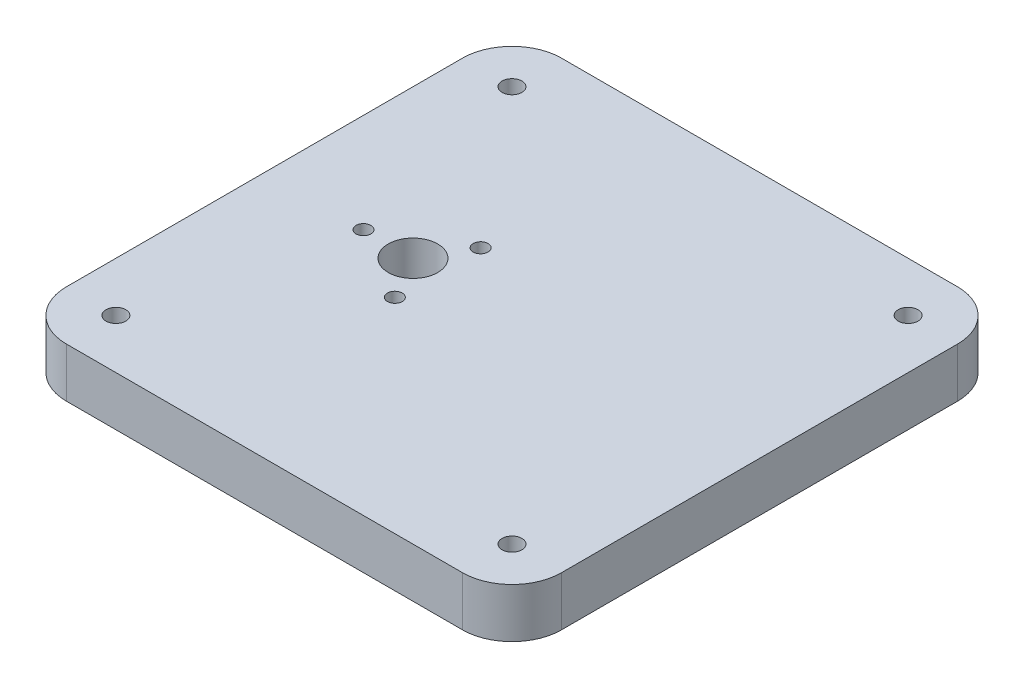
SolidWorks part; units mm, degrees
ref_plane "前视基准面" through (0, 0, 0) normal (0, 0, 1) x (1, 0, 0)
ref_plane "上视基准面" through (0, 0, 0) normal (0, 1, 0) x (1, 0, 0)
ref_plane "右视基准面" through (0, 0, 0) normal (1, 0, 0) x (0, 0, -1)
sketch "草图1" plane through (0, 0, 0) normal (0, 1, 0) x (1, 0, 0)
  line L1 (-50.9375, 34.9609) -> (29.0625, 34.9609)
  line L2 (-60.9375, 24.9609) -> (-60.9375, -55.0391)
  line L3 (-50.9375, -65.0391) -> (29.0625, -65.0391)
  line L4 (39.0625, 24.9609) -> (39.0625, -55.0391)
  arc A0 (-60.9375, 24.9609) -> (-50.9375, 34.9609) centre (-50.9375, 24.9609) cw
  arc A1 (-60.9375, -55.0391) -> (-50.9375, -65.0391) centre (-50.9375, -55.0391) ccw
  arc A2 (29.0625, -65.0391) -> (39.0625, -55.0391) centre (29.0625, -55.0391) ccw
  arc A3 (29.0625, 34.9609) -> (39.0625, 24.9609) centre (29.0625, 24.9609) cw
  circle A4 centre (-50.9375, 24.9609) radius 2
  circle A5 centre (-50.9375, -55.0391) radius 2
  circle A6 centre (29.0625, 24.9609) radius 2
  circle A7 centre (29.0625, -55.0391) radius 2
  circle A8 centre (-30.9375, -15.0391) radius 5
  circle A10 centre (-40.9375, -15.0391) radius 1.5
  circle A11 centre (-25.9375, -23.6993) radius 1.5
  circle A12 centre (-25.9375, -6.3788) radius 1.5
  point P6 (-60.9375, 34.9609)
  point P11 (39.0625, -65.0391)
  point P14 (39.0625, 34.9609)
  dimension "D3" = 10
  dimension "D4" = 10
  dimension "D5" = 10
  dimension "D6" = 10
  dimension "D1" = 100
  dimension "D2" = 100
extrude "凸台-拉伸1" add sketch "草图1" along normal blind 10
